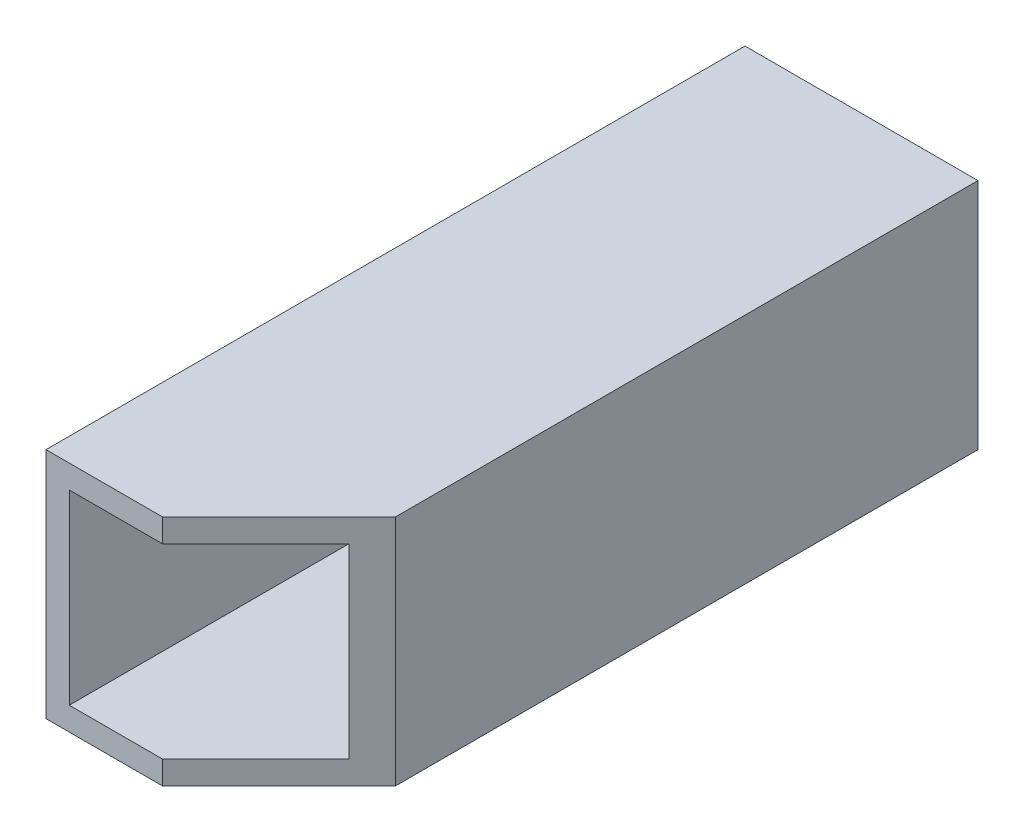
SolidWorks part; units mm, degrees
ref_plane "Front Plane" through (0, 0, 0) normal (0, 0, 1) x (1, 0, 0)
ref_plane "Top Plane" through (0, 0, 0) normal (0, 1, 0) x (1, 0, 0)
ref_plane "Right Plane" through (0, 0, 0) normal (1, 0, 0) x (0, 0, -1)
sketch "Sketch2" plane through (0, 0, 0) normal (0, 0, -1) x (1, 0, 0)
  line L0 (-20, -20) -> (-20, 20)
  line L1 (-25, -25) -> (25, -25)
  line L2 (-25, -25) -> (-25, 25)
  line L3 (-25, 25) -> (25, 25)
  line L4 (25, -25) -> (25, 25)
  line L5 (-20, 20) -> (20, 20)
  line L6 (20, -20) -> (20, 20)
  line L7 (-20, -20) -> (20, -20)
  dimension "tube_width" = 50
  dimension "tube_height" = 50
  dimension "D1" = 25
  dimension "D3" = 25
  dimension "D2" = 5
extrude "Boss-Extrude1" add sketch "Sketch2" against normal blind 150
sketch "Sketch3" plane through (0, -25, 0) normal (0, -1, 0) x (1, 0, 0)
  line L0 (0, 150) -> (25, 125)
  line L1 (25, 150) -> (-25, 150) construction
  line L2 (25, 150) -> (25, 0) construction
  line L3 (25, 125) -> (25, 150)
  line L4 (25, 150) -> (0, 150)
  dimension "D1" = 45
extrude "Cut-Extrude1" cut sketch "Sketch3" against normal through all
equation "\"D1@Sketch2\"=\"tube_width@Sketch2\"/2"
equation "\"D3@Sketch2\"=\"tube_height@Sketch2\"/2"
